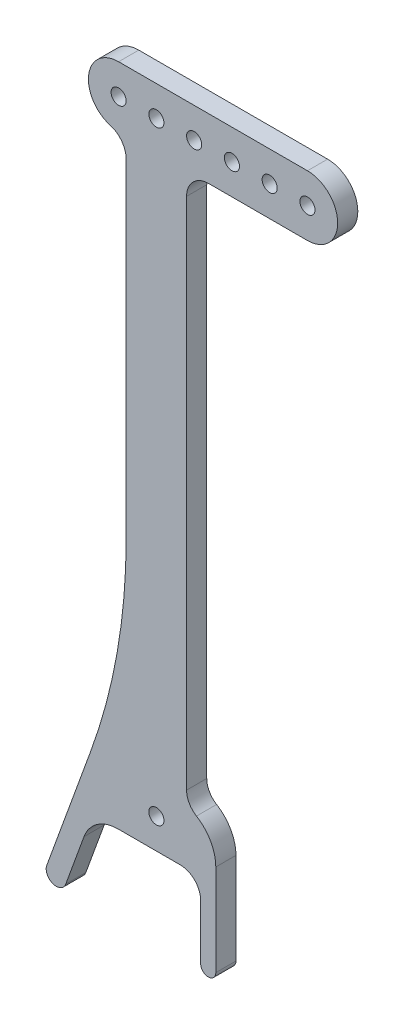
SolidWorks part; units mm, degrees
material "6061-T6 (SS)"
ref_plane "Front Plane" through (0, 0, 0) normal (0, 0, 1) x (1, 0, 0)
ref_plane "Top Plane" through (0, 0, 0) normal (0, 1, 0) x (1, 0, 0)
ref_plane "Right Plane" through (0, 0, 0) normal (1, 0, 0) x (0, 0, -1)
sketch "Sketch1" plane through (0, 0, 0) normal (0, 0, 1) x (1, 0, 0)
  line L0 (-11.9063, 200.025) -> (51.9933, 200.025) construction
  line L2 (0, 80.3743) -> (0, 184.1699)
  line L4 (19.05, 21.408) -> (19.05, 183.515)
  line L7 (-2.3813, 209.55) -> (57.15, 209.55)
  line L10 (9.525, 9.525) -> (9.525, 11.9062) construction
  line L11 (26.035, 190.5) -> (57.15, 190.5)
  line L12 (9.525, 200.025) -> (9.525, 197.6438) construction
  line L13 (0, -55) -> (0, 55) construction
  line L14 (9.525, 11.9062) -> (9.525, 9.525) construction
  line L15 (-35.8837, -19.05) -> (54.9337, -19.05) construction
  line L17 (23.495, -23.8125) -> (23.495, -6.477)
  line L19 (28.2575, -23.8125) -> (28.2575, 5.0261)
  line L20 (-2.6386, 0) -> (17.018, 0)
  line L21 (-13.2847, -7.4545) -> (-19.056, -23.3109)
  line L22 (-11.2057, 16.8237) -> (-25.023, -21.1391)
  circle A0 centre (9.525, 9.525) radius 2.3813
  circle A2 centre (9.525, 200.025) radius 2.3812
  circle A3 centre (21.4312, 200.025) radius 2.3813
  circle A4 centre (-2.3813, 200.025) radius 2.3812
  circle A5 centre (33.3375, 200.025) radius 2.3812
  circle A6 centre (57.15, 200.025) radius 2.3812
  arc A7 (57.15, 209.55) -> (57.15, 190.5) centre (57.15, 200.025) cw
  arc A8 (-5.0373, 190.8778) -> (-2.3813, 209.55) centre (-2.3813, 200.025) cw
  arc A9 (19.05, 183.515) -> (26.035, 190.5) centre (26.035, 183.515) cw
  arc A10 (-5.0373, 190.8778) -> (0, 184.1699) centre (-6.985, 184.1699) cw
  circle A11 centre (45.2437, 200.025) radius 2.3812
  circle A12 centre (9.525, -19.05) radius 12.7 construction
  arc A13 (23.495, -23.8125) -> (28.2575, -23.8125) centre (25.8763, -23.8125) ccw
  arc A14 (17.018, 0) -> (23.495, -6.477) centre (17.018, -6.477) cw
  arc A15 (19.05, 21.408) -> (22.1598, 15.875) centre (25.527, 21.408) ccw
  arc A16 (22.1598, 15.875) -> (28.2575, 5.0261) centre (15.5575, 5.0261) cw
  arc A17 (-2.6386, 0) -> (-13.2847, -7.4545) centre (-2.6386, -11.3294) ccw
  arc A18 (0, 80.3743) -> (-11.2057, 16.8237) centre (-185.8097, 80.3743) cw
  arc A19 (-19.056, -23.3109) -> (-25.023, -21.1391) centre (-22.0395, -22.225) cw
  point P15 (-6.985, 27.7571)
  point P16 (0, 55.0639)
  point P44 (9.525, -19.05)
  point P52 (-11.9063, 17.0787)
  point P53 (0, 0)
  dimension "D3" = 4.7625
  dimension "D4" = 19.05
  dimension "D2" = 4.7625
  dimension "D5" = 11.9062
  dimension "D8" = 11.9062
  dimension "D9" = 190.5
  dimension "D10" = 6.985
  dimension "D11" = 6.985
  dimension "D13" = 11.9062
  dimension "D14" = 28.575
  dimension "D15" = 25.4
  dimension "D17" = 13.97
  dimension "D16" = 2.3813
  dimension "D19" = 6.477
  dimension "D21" = 12.7
  dimension "D20" = 6.477
  dimension "D23" = 6.35
  dimension "D26" = 31.75
  dimension "D30" = 11.3294
  dimension "D6" = 11.9062
  dimension "D7" = 11.9062
  dimension "D12" = 19.05
  dimension "D18" = 4.7625
  dimension "D22" = 6.35
  dimension "D24" = 70
  dimension "D25" = 25.4
  dimension "D28" = 9.525
  dimension "D29" = 9.525
  dimension "D31" = 9.525
extrude "Boss-Extrude1" add sketch "Sketch1" along normal blind 6.35
